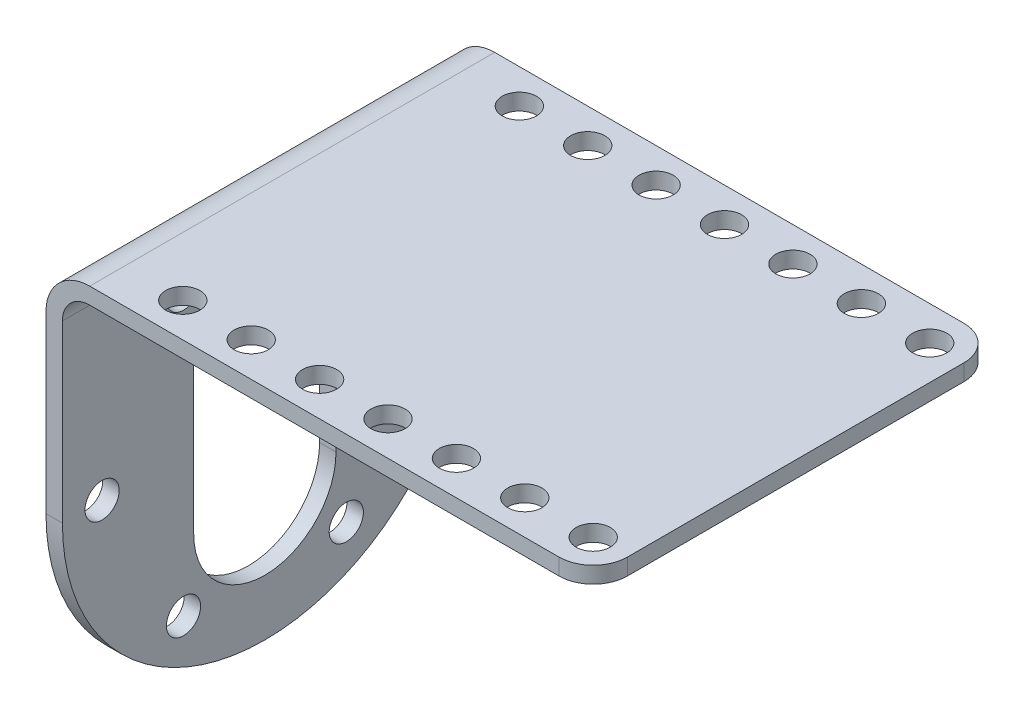
SolidWorks part; units mm, degrees
ref_plane "Front Plane" through (0, 0, 0) normal (0, 0, 1) x (1, 0, 0)
ref_plane "Top Plane" through (0, 0, 0) normal (0, 1, 0) x (1, 0, 0)
ref_plane "Right Plane" through (0, 0, 0) normal (1, 0, 0) x (0, 0, -1)
sketch "Sketch1" plane through (0, 0, 0) normal (0, 0, 1) x (1, 0, 0)
  line L0 (0, 0) -> (0, 35.052)
  line L1 (4.064, 39.116) -> (50.8, 39.116)
  line L2 (50.8, 39.116) -> (50.8, 37.592)
  line L3 (50.8, 37.592) -> (4.064, 37.592)
  line L4 (1.524, 35.052) -> (1.524, 0)
  line L5 (1.524, 0) -> (0, 0)
  arc A0 (4.064, 37.592) -> (1.524, 35.052) centre (4.064, 35.052) ccw
  arc A1 (0, 35.052) -> (4.064, 39.116) centre (4.064, 35.052) cw
  point P6 (50.8, 39.116)
  point P8 (51.4773, 38.9572)
  point P11 (1.524, 37.592)
  dimension "D4" = 2.54
  dimension "D1" = 1.524
  dimension "D2" = 37.592
  dimension "D3" = 49.276
extrude "Boss-Extrude1" add sketch "Sketch1" along normal mid plane 37.592
sketch "Sketch2" plane through (0, 0, 0) normal (-1, 0, 0) x (0, 0, 1)
  line L4 (-18.796, 35.052) -> (-18.796, 0)
  line L5 (-18.796, 0) -> (18.796, 0)
  line L6 (18.796, 0) -> (18.796, 35.052)
  line L7 (18.796, 35.052) -> (-18.796, 35.052)
  line L8 (-18.796, 18.796) -> (-18.796, 0)
  line L9 (-18.796, 0) -> (18.796, 0)
  line L10 (18.796, 0) -> (18.796, 18.796)
  line L12 (18.796, 35.052) -> (-18.796, 35.052)
  arc A0 (-18.796, 18.796) -> (18.796, 18.796) centre (0, 18.796) ccw
  point P2 (0, 0)
  line M6 (-18.796, 35.052) -> (-18.796, 0)
  line M7 (-18.796, 0) -> (18.796, 0)
  line M8 (18.796, 0) -> (18.796, 35.052)
  dimension "D1" = 0
extrude "Cut-Extrude1" cut sketch "Sketch2" against normal through all contours A0 M6 M7 | A0 L9 M8
sketch "Sketch3" plane through (0, 0, 0) normal (-1, 0, 0) x (0, 0, 1)
  line L0 (0, 11.811) -> (0, 25.781) construction
  line L1 (-6.604, 11.811) -> (-6.604, 25.781)
  line L2 (6.604, 11.811) -> (6.604, 25.781)
  arc A0 (-6.604, 11.811) -> (6.604, 11.811) centre (0, 11.811) ccw
  arc A1 (6.604, 25.781) -> (-6.604, 25.781) centre (0, 25.781) ccw
  arc A2 (-18.796, 18.796) -> (18.796, 18.796) centre (0, 18.796) ccw construction
  point P3 (0, 18.796)
  dimension "D1" = 13.208
  dimension "D2" = 13.97
extrude "Cut-Extrude2" cut sketch "Sketch3" against normal through all
sketch "Sketch4" plane through (0, 0, 0) normal (-1, 0, 0) x (0, 0, 1)
  line L1 (15.113, 18.796) -> (7.5565, 31.8842) construction
  line L2 (7.5565, 31.8842) -> (-7.5565, 31.8842) construction
  line L3 (-7.5565, 31.8842) -> (-15.113, 18.796) construction
  line L4 (-15.113, 18.796) -> (-7.5565, 5.7078) construction
  line L5 (-7.5565, 5.7078) -> (7.5565, 5.7078) construction
  line L6 (7.5565, 5.7078) -> (15.113, 18.796) construction
  circle A0 centre (0, 18.796) radius 13.0882 construction
  arc A1 (-18.796, 18.796) -> (18.796, 18.796) centre (0, 18.796) ccw construction
  point P1 (0, 19.6498)
  point P12 (8.049, 4.8547)
  dimension "D1" = 15.113
hole_wizard "1/8 (0.125) Diameter Hole2" positions "3DSketch1" profile "Sketch6" hole size "1/8" standard "ANSI Inch" end condition through all
sketch3d "3DSketch1"
  point P0 (0, 31.8842, -7.5565)
  point P3 (0, 31.8842, 7.5565)
  point P6 (0, 18.796, 15.113)
  point P9 (0, 5.7078, 7.5565)
  point P12 (0, 5.7078, -7.5565)
  point P15 (0, 18.796, -15.113)
sketch "Sketch6" plane through (0, 31.8842, -7.5565) normal (0, 1, 0) x (0, 0, 1)
  line L0 (0, 0) -> (0, 50.8)
  line L1 (0, 50.8) -> (1.5875, 50.8)
  line L2 (1.5875, 50.8) -> (1.5875, 0)
  line L5 (1.5875, 0) -> (0, 0)
  line L11 (0, -6.35) -> (0, 107.95) construction
  dimension "Thru Hole Dia." = 3.175
  dimension "Thru Hole Depth" = 50.8
fillet "Fillet1" radius 3.175 2 edges at (50.8, 38.354, -18.796) (50.8, 38.354, 18.796)
sketch "Sketch7" plane through (0, 39.116, 0) normal (0, 1, 0) x (1, 0, 0)
  line L0 (0, 0) -> (47.625, 0) construction
  line L1 (47.625, -15.621) -> (47.625, 15.621) construction
  line L2 (50.8, -15.621) -> (50.8, 15.621) construction
  point P5 (47.625, 0)
  dimension "D1" = 31.242
  dimension "D2" = 3.175
hole_wizard "1/8 (0.125) Diameter Hole1" positions "3DSketch2" profile "Sketch8" hole size "1/8" standard "ANSI Inch" end condition through all
sketch3d "3DSketch2"
  point P0 (47.625, 39.116, -15.621)
sketch "Sketch8" plane through (47.625, 39.116, -15.621) normal (1, 0, 0) x (0, 0, 1)
  line L0 (0, 0) -> (0, 39.116)
  line L1 (0, 39.116) -> (1.5875, 39.116)
  line L2 (1.5875, 39.116) -> (1.5875, 0)
  line L5 (1.5875, 0) -> (0, 0)
  line L11 (0, -6.35) -> (0, 107.95) construction
  dimension "Thru Hole Dia." = 3.175
  dimension "Thru Hole Depth" = 39.116
pattern_linear "LPattern1" count 7 spacing 6.35 along (-1, 0, 0) of "1/8 (0.125) Diameter Hole1"
mirror "Mirror1" about plane through (0, 0, 0) normal (0, 0, 1) of "LPattern1", "1/8 (0.125) Diameter Hole1"
